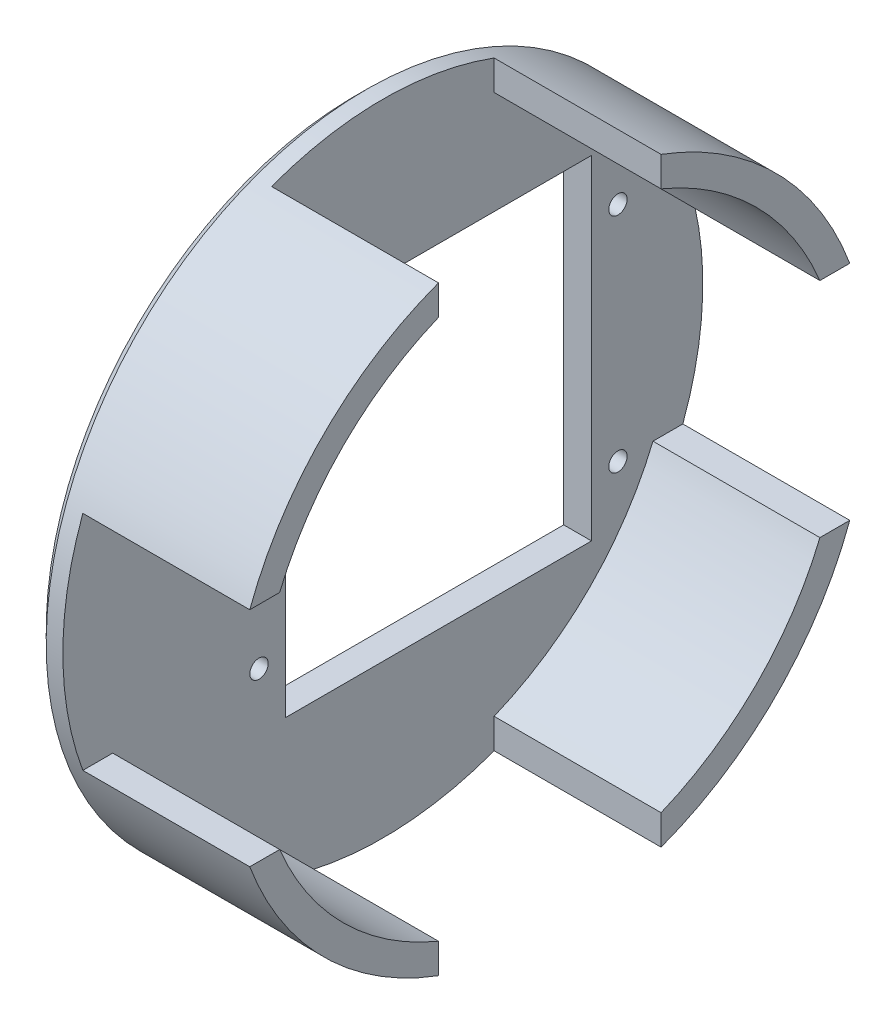
SolidWorks part; units mm, degrees
material "ﾎﾟﾘｴﾁﾚﾝｲﾐﾝ(PEI)"
ref_plane "正面" through (0, 0, 0) normal (0, 0, 1) x (1, 0, 0)
ref_plane "平面" through (0, 0, 0) normal (0, 1, 0) x (1, 0, 0)
ref_plane "右側面" through (0, 0, 0) normal (1, 0, 0) x (0, 0, -1)
sketch "ｽｹｯﾁ1" plane through (0, 0, 0) normal (1, 0, 0) x (0, 0, -1)
  circle A4 centre (0, 0) radius 57.5
  dimension "D4" = 115
extrude "ﾎﾞｽ - 押し出し1" add sketch "ｽｹｯﾁ1" along normal blind 5
sketch "ｽｹｯﾁ2" plane through (5, 0, 0) normal (1, 0, 0) x (0, 0, -1)
  circle A0 centre (0, 0) radius 52.5
  circle A1 centre (0, 0) radius 57.5
  circle A2 centre (0, 0) radius 57.5
  dimension "D1" = 0
  dimension "D2" = 5
extrude "ﾎﾞｽ - 押し出し2" add sketch "ｽｹｯﾁ2" along normal blind 30
sketch "ｽｹｯﾁ3" plane through (5, 0, 0) normal (1, 0, 0) x (0, 0, -1)
  line L0 (0, 0) -> (10, 0) construction
  line L1 (10, 20) -> (10, -20) construction
  line L2 (42.25, 20) -> (-22.25, 20) construction
  line L3 (42.25, 20) -> (42.25, -20) construction
  line L4 (42.25, -20) -> (-22.25, -20) construction
  line L5 (-22.25, 20) -> (-22.25, -20) construction
  line L6 (42.25, 20) -> (-22.25, -20) construction
  line L7 (42.25, -20) -> (-22.25, 20) construction
  line L8 (-22.25, 0) -> (42.25, 0) construction
  line L14 (-17.5, 30) -> (37.5, 30)
  line L15 (-17.5, 30) -> (-17.5, -30)
  line L16 (-17.5, -30) -> (37.5, -30)
  line L17 (37.5, 30) -> (37.5, -30)
  line L18 (-17.5, 30) -> (37.5, -30) construction
  line L19 (-17.5, -30) -> (37.5, 30) construction
  circle A0 centre (-22.25, 20) radius 1.65
  circle A1 centre (-22.25, -20) radius 1.65
  circle A2 centre (42.25, 20) radius 1.65
  circle A3 centre (42.25, -20) radius 1.65
  dimension "D4" = 3.3
  dimension "D5" = 55
  dimension "D1" = 10
  dimension "D2" = 64.5
  dimension "D3" = 40
  dimension "D6" = 60
extrude "ｶｯﾄ - 押し出し1" cut sketch "ｽｹｯﾁ3" against normal through all
sketch "ｽｹｯﾁ4" plane through (35, 0, 0) normal (1, 0, 0) x (0, 0, -1)
  line L1 (-20, 53.9096) -> (20, 53.9096)
  line L2 (-20, 53.9096) -> (-20, -53.9096)
  line L3 (-20, -53.9096) -> (20, -53.9096)
  line L4 (20, 53.9096) -> (20, -53.9096)
  line L5 (-20, 53.9096) -> (20, -53.9096) construction
  line L6 (-20, -53.9096) -> (20, 53.9096) construction
  line L7 (-53.9096, 20) -> (53.9096, 20)
  line L8 (-53.9096, 20) -> (-53.9096, -20)
  line L9 (-53.9096, -20) -> (53.9096, -20)
  line L10 (53.9096, 20) -> (53.9096, -20)
  line L11 (-53.9096, 20) -> (53.9096, -20) construction
  line L12 (-53.9096, -20) -> (53.9096, 20) construction
  circle A0 centre (0, 0) radius 57.5 construction
  circle A2 centre (0, 0) radius 57.5
  circle A3 centre (0, 0) radius 57.5
  point P0 (0, 0)
  point P8 (0, 0)
  circle M4 centre (0, 0) radius 57.5
  circle M5 centre (0, 0) radius 52.5
  dimension "D1" = 40
  dimension "D2" = 0
extrude "ｶｯﾄ - 押し出し2" cut sketch "ｽｹｯﾁ4" against normal blind 30 contours L8 L9 L7 M5 | L8 M4 | L4 L1 L2 M5 | L1 M4 | L10 L7 L9 M5 | L10 M4 | L3 M4 | L4 L2 L3 M5 | A3
chamfer "面取り1" distance 2 angle 45 1 edges at (0, 0, -57.5)
